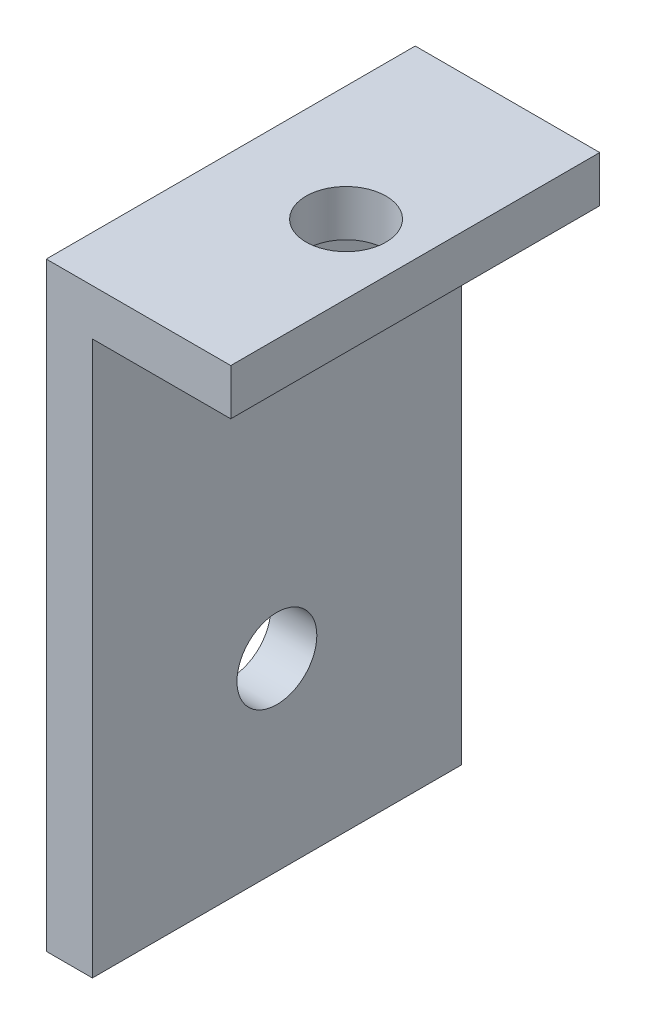
SolidWorks part; units mm, degrees
ref_plane "Front Plane" through (0, 0, 0) normal (0, 0, 1) x (1, 0, 0)
ref_plane "Top Plane" through (0, 0, 0) normal (0, 1, 0) x (1, 0, 0)
ref_plane "Right Plane" through (0, 0, 0) normal (1, 0, 0) x (0, 0, -1)
sketch "Sketch2" plane through (0, 0, 0) normal (0, 0, 1) x (1, 0, 0)
  line L0 (0, 0) -> (0, 41.275)
  line L1 (0, 41.275) -> (12.7, 41.275)
  line L2 (12.7, 41.275) -> (12.7, 38.1)
  line L3 (12.7, 38.1) -> (3.175, 38.1)
  line L4 (3.175, 38.1) -> (3.175, 0)
  line L5 (3.175, 0) -> (0, 0)
  dimension "D1" = 3.175
  dimension "D2" = 3.175
  dimension "D3" = 12.7
  dimension "D4" = 38.1
extrude "Boss-Extrude1" add sketch "Sketch2" along normal blind 25.4
sketch "Sketch3" plane through (0, 38.1, 0) normal (0, -1, 0) x (1, 0, 0)
  line L0 (12.7, 25.4) -> (12.7, 0) construction
  line L1 (3.175, 0) -> (12.7, 0) construction
  point P0 (7.9375, 12.7)
  dimension "D1" = 4.7625
  dimension "D2" = 12.7
hole_wizard "M5 Clearance Hole1" positions "Sketch4" profile "Sketch5" hole size "M5" standard "ANSI Metric" end condition through all
sketch "Sketch4" plane through (0, 38.1, 0) normal (0, -1, 0) x (-1, 0, 0)
  point P0 (-7.9375, -12.7)
sketch "Sketch5" plane through (7.9375, 38.1, 12.7) normal (1, 0, 0) x (0, 0, -1)
  line L0 (0, 0) -> (0, 3.175)
  line L1 (0, 3.175) -> (2.75, 3.175)
  line L2 (2.75, 3.175) -> (2.75, 0)
  line L5 (2.75, 0) -> (0, 0)
  line L11 (0, -6.35) -> (0, 107.95) construction
  dimension "Thru Hole Dia." = 5.5
  dimension "Thru Hole Depth" = 3.175
sketch "Sketch6" plane through (3.175, 0, 0) normal (1, 0, 0) x (0, 0, -1)
  line L0 (-25.4, 0) -> (0, 0) construction
  line L1 (0, 0) -> (0, 38.1) construction
  point P0 (-12.7, 12.7)
  dimension "D1" = 12.7
  dimension "D2" = 12.7
hole_wizard "M5 Clearance Hole2" positions "Sketch7" profile "Sketch8" hole size "M5" standard "ANSI Metric" end condition through all
sketch "Sketch7" plane through (3.175, 0, 0) normal (1, 0, 0) x (0, 0, -1)
  point P0 (-12.7, 12.7)
sketch "Sketch8" plane through (3.175, 12.7, 12.7) normal (0, 1, 0) x (0, 0, -1)
  line L0 (0, 0) -> (0, 3.175)
  line L1 (0, 3.175) -> (2.75, 3.175)
  line L2 (2.75, 3.175) -> (2.75, 0)
  line L5 (2.75, 0) -> (0, 0)
  line L11 (0, -6.35) -> (0, 107.95) construction
  dimension "Thru Hole Dia." = 5.5
  dimension "Thru Hole Depth" = 3.175
